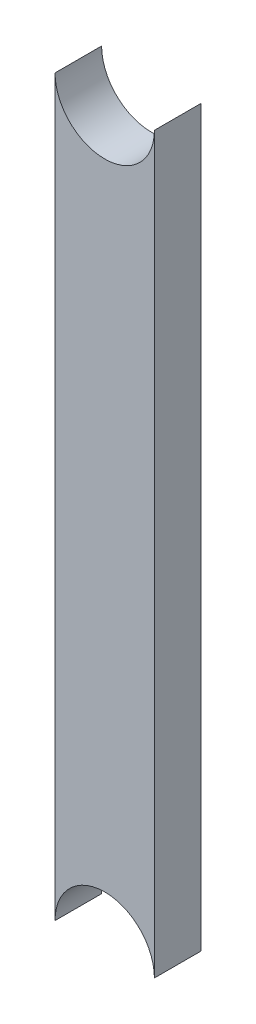
SolidWorks part; units mm, degrees
material "Titanium"
ref_plane "Front Plane" through (0, 0, 0) normal (0, 0, 1) x (1, 0, 0)
ref_plane "Top Plane" through (0, 0, 0) normal (0, 1, 0) x (1, 0, 0)
ref_plane "Right Plane" through (0, 0, 0) normal (1, 0, 0) x (0, 0, -1)
sketch "Sketch1" plane through (0, 0, 0) normal (0, 0, 1) x (1, 0, 0)
  line L1 (-3.2, 0) -> (-3.2, 47.2744)
  line L2 (3.2, 47.2744) -> (3.2, 0)
  line L3 (0, -1.65) -> (0, 1.65) construction
  arc A2 (3.2, 0) -> (-3.2, 0) centre (0, 0) ccw
  arc A3 (-3.2, 47.2744) -> (3.2, 47.2744) centre (0, 47.2744) ccw
  dimension "D1" = 6.4
  dimension "D2" = 47.2744
extrude "Boss-Extrude3" add sketch "Sketch1" along normal blind 3
equation "\"bScale\"= 8"
equation "\"lScale\"= 8"
equation "\"D1@Sketch1\"=.8*\"bScale\""
equation "\"D2@Sketch1\"=5.9093mm*\"lScale\""
